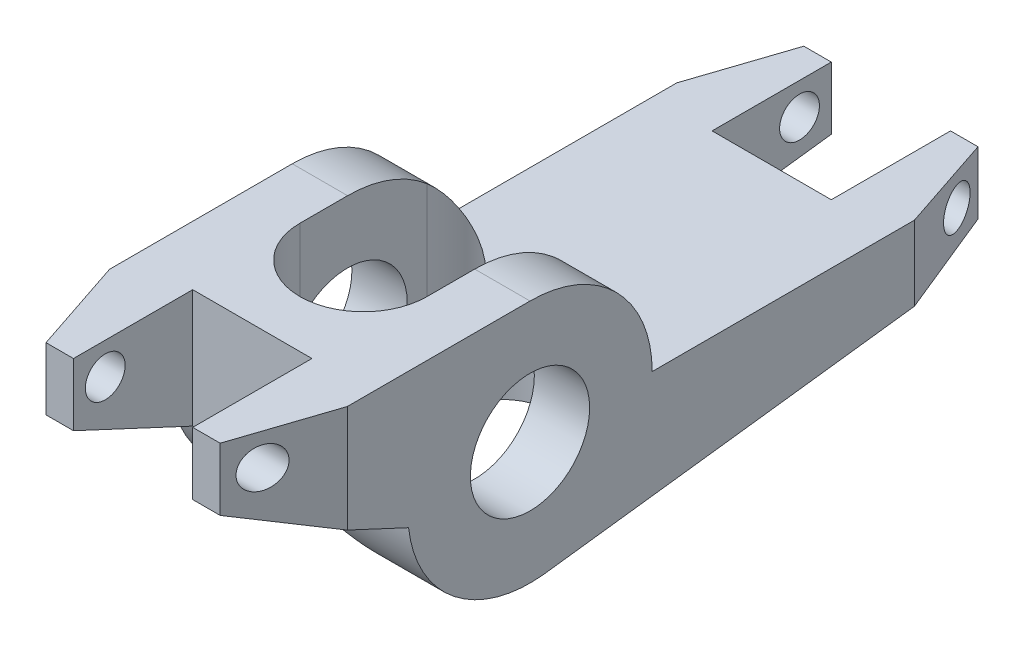
SolidWorks part; units mm, degrees
ref_plane "Front Plane" through (0, 0, 0) normal (0, 0, 1) x (1, 0, 0)
ref_plane "Top Plane" through (0, 0, 0) normal (0, 1, 0) x (1, 0, 0)
ref_plane "Right Plane" through (0, 0, 0) normal (1, 0, 0) x (0, 0, -1)
sketch "Sketch2" plane through (0, 0, 0) normal (1, 0, 0) x (0, 0, -1)
  line L0 (0, 9.765) -> (-22.225, 9.765)
  line L1 (-22.225, 9.765) -> (-22.225, 4.765)
  line L2 (-22.225, 4.765) -> (-9.7059, -1.0728)
  line L3 (9.765, 0) -> (38.345, 0)
  line L4 (38.345, 0) -> (38.345, -5)
  line L5 (38.345, -5) -> (1.2235, -9.688)
  circle A0 centre (0, 0) radius 4.765
  arc A1 (9.765, 0) -> (0, 9.765) centre (0, 0) ccw
  arc A2 (-9.7059, -1.0728) -> (1.2235, -9.688) centre (0, 0) ccw
  dimension "D1" = 9.53
  dimension "D2" = 5
  dimension "D3" = 5
  dimension "D4" = 22.225
  dimension "D5" = 25
  dimension "D6" = 5
  dimension "D7" = 28.58
extrude "Boss-Extrude1" add sketch "Sketch2" along normal mid plane 19
chamfer "Chamfer1" distance 2.54 distance2 7.62 2 edges at (9.5, -2.5, -38.345) (9.5, 7.265, 22.225)
chamfer "Chamfer2" distance 7.62 distance2 2.54 2 edges at (-9.5, -2.5, -38.345) (-9.5, 7.265, 22.225)
sketch "Sketch3" plane through (0, 0, 0) normal (0, 1, 0) x (1, 0, 0)
  line L0 (0, -3.81) -> (0, 6.35) construction
  line L1 (-5.08, -3.81) -> (-5.08, 6.35)
  line L2 (5.08, -3.81) -> (5.08, 6.35)
  arc A0 (-5.08, -3.81) -> (5.08, -3.81) centre (0, -3.81) ccw
  arc A1 (5.08, 6.35) -> (-5.08, 6.35) centre (0, 6.35) ccw
  point P3 (0, 1.27)
  dimension "D1" = 10.16
  dimension "D2" = 10.16
  dimension "D3" = 3.81
extrude "Cut-Extrude1" cut sketch "Sketch3" against normal through all both and the other way through all
sketch "Sketch4" plane through (0, 0, 0) normal (0, 1, 0) x (1, 0, 0)
  line L0 (6.96, 38.345) -> (-6.96, 38.345) construction
  line L1 (4.765, 28.815) -> (-4.765, 28.815)
  line L2 (4.765, 28.815) -> (4.765, 38.345)
  line L3 (4.765, 38.345) -> (-4.765, 38.345)
  line L4 (-4.765, 28.815) -> (-4.765, 38.345)
  line L5 (4.765, 28.815) -> (-4.765, 38.345) construction
  line L6 (4.765, 38.345) -> (-4.765, 28.815) construction
  line L7 (6.96, -22.225) -> (-6.96, -22.225) construction
  line L8 (-4.765, -12.695) -> (4.765, -12.695)
  line L9 (-4.765, -12.695) -> (-4.765, -22.225)
  line L10 (-4.765, -22.225) -> (4.765, -22.225)
  line L11 (4.765, -12.695) -> (4.765, -22.225)
  line L12 (-4.765, -12.695) -> (4.765, -22.225) construction
  line L13 (-4.765, -22.225) -> (4.765, -12.695) construction
  point P0 (0, 33.58)
  point P7 (0, -17.46)
  dimension "D1" = 9.53
  dimension "D2" = 9.53
extrude "Cut-Extrude2" cut sketch "Sketch4" against normal through all both and the other way through all
sketch "Sketch5" plane through (0, 0, 0) normal (1, 0, 0) x (0, 0, -1)
  line L0 (30.725, 0) -> (38.345, 0) construction
  line L1 (38.345, 0) -> (38.345, -5) construction
  line L2 (-14.605, 9.765) -> (-22.225, 9.765) construction
  line L3 (-22.225, 9.765) -> (-14.605, 9.765) construction
  line L4 (-22.225, 4.765) -> (-22.225, 9.765) construction
  circle A0 centre (35.805, -2.54) radius 1.59
  circle A1 centre (-19.685, 7.225) radius 1.59
  point P8 (-18.415, 9.765)
  dimension "D1" = 3.18
  dimension "D4" = 2.54
  dimension "D2" = 2.54
  dimension "D3" = 2.54
  dimension "D5" = 2.54
extrude "Cut-Extrude3" cut sketch "Sketch5" against normal through all both and the other way through all
